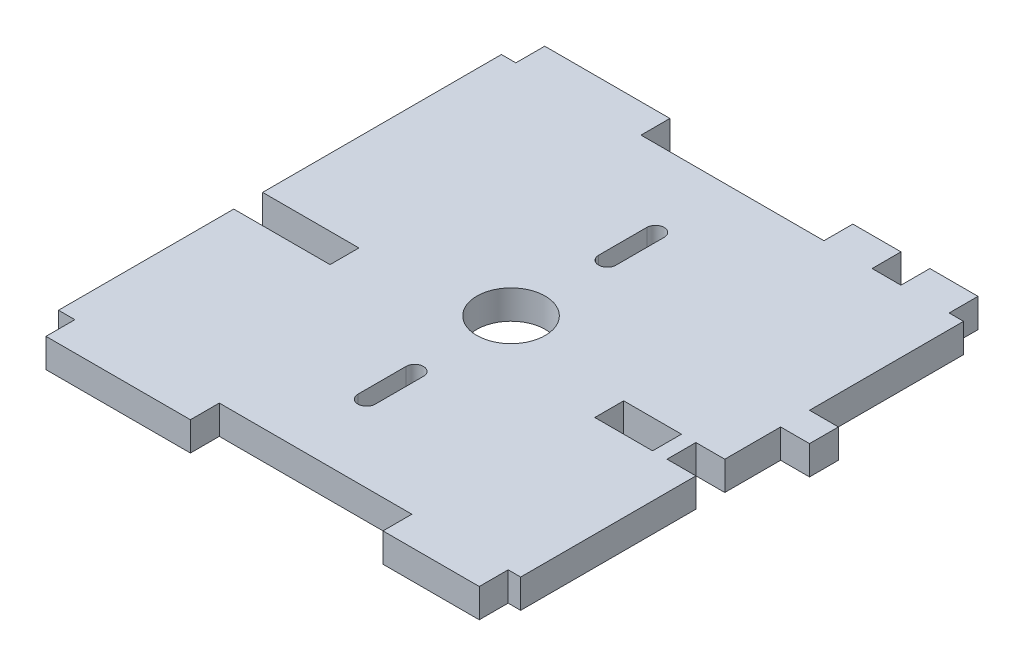
SolidWorks part; units mm, degrees
material "Acrílico (médio-alto impacto)"
ref_plane "Plano frontal" through (0, 0, 0) normal (0, 0, 1) x (1, 0, 0)
ref_plane "Plano superior" through (0, 0, 0) normal (0, 1, 0) x (1, 0, 0)
ref_plane "Plano direito" through (0, 0, 0) normal (1, 0, 0) x (0, 0, -1)
sketch "Esboço1" plane through (0, 0, 0) normal (0, 1, 0) x (1, 0, 0)
  line L1 (-24, -23) -> (24, -23)
  line L2 (-24, -23) -> (-24, 23)
  line L3 (-24, 23) -> (24, 23)
  line L4 (24, -23) -> (24, 23)
  line L5 (0, 23) -> (0, -23) construction
  line L6 (-24, 0) -> (24, 0) construction
  point P0 (0, 0)
  dimension "D1" = 46
  dimension "D2" = 48
sketch "Esboço2" plane through (0, 0, 0) normal (0, 1, 0) x (1, 0, 0)
  line L0 (0, 23) -> (0, -23) construction
  circle A0 centre (0, 0) radius 3.55
  dimension "D1" = 7.1
sketch "Esboço3" plane through (0, 0, 0) normal (0, 1, 0) x (1, 0, 0)
  line L0 (0, 10) -> (0, 15) construction
  line L1 (0, 23) -> (0, -23) construction
  line L2 (-0.9, 10) -> (-0.9, 15)
  line L3 (0.9, 10) -> (0.9, 15)
  arc A0 (-0.9, 10) -> (0.9, 10) centre (0, 10) ccw
  arc A1 (0.9, 15) -> (-0.9, 15) centre (0, 15) ccw
  circle A2 centre (0, 0) radius 12.5 construction
  point P4 (0, 12.5)
  dimension "D1" = 25
  dimension "D2" = 1.8
  dimension "D3" = 5
sketch "Esboço5" plane through (0, 0, 0) normal (0, 1, 0) x (1, 0, 0)
  line L0 (-24, 23) -> (24, 23) construction
  line L1 (22.5, 26) -> (17.5, 26)
  line L2 (22.5, 26) -> (22.5, 23)
  line L3 (22.5, 23) -> (17.5, 23)
  line L4 (17.5, 26) -> (17.5, 23)
  line L5 (14.5, 26) -> (9.5, 26)
  line L6 (14.5, 26) -> (14.5, 23)
  line L7 (14.5, 23) -> (9.5, 23)
  line L8 (9.5, 26) -> (9.5, 23)
  line L9 (-9.5, 26) -> (-22.5, 26)
  line L10 (-9.5, 26) -> (-9.5, 23)
  line L11 (-9.5, 23) -> (-22.5, 23)
  line L12 (-22.5, 26) -> (-22.5, 23)
  line L13 (-24, -23) -> (-24, 23) construction
  dimension "D1" = 1.5
  dimension "D2" = 1.5
  dimension "D3" = 3
  dimension "D4" = 5
  dimension "D5" = 3
  dimension "D6" = 13
sketch "Esboço6" plane through (0, 0, 0) normal (0, 1, 0) x (1, 0, 0)
  line L0 (24, -23) -> (24, 23) construction
  line L1 (24, 4) -> (27, 4)
  line L2 (24, 4) -> (24, 7)
  line L3 (24, 7) -> (27, 7)
  line L4 (27, 4) -> (27, 7)
  line L5 (-24, 23) -> (24, 23) construction
  dimension "D1" = 3
  dimension "D2" = 16
sketch "Esboço7" plane through (0, 0, 0) normal (0, 1, 0) x (1, 0, 0)
  line L0 (-24, -23) -> (-24, 23) construction
  line L1 (24, -4.8) -> (21, -4.8)
  line L2 (24, -4.8) -> (24, -1.8)
  line L3 (24, -1.8) -> (21, -1.8)
  line L4 (21, -4.8) -> (21, -1.8)
  line L5 (19.5, -4.8) -> (13.5, -4.8)
  line L6 (19.5, -4.8) -> (19.5, -1.8)
  line L7 (19.5, -1.8) -> (13.5, -1.8)
  line L8 (13.5, -4.8) -> (13.5, -1.8)
  line L9 (-14, -4.8) -> (-24, -4.8)
  line L10 (-14, -4.8) -> (-14, -1.8)
  line L11 (-14, -1.8) -> (-24, -1.8)
  line L12 (-24, -4.8) -> (-24, -1.8)
  line L13 (24, -23) -> (24, 23) construction
  line L19 (-24, -23) -> (24, -23) construction
  dimension "D1" = 3
  dimension "D2" = 18.2
  dimension "D3" = 10
  dimension "D4" = 3
  dimension "D5" = 1.5
  dimension "D6" = 6
extrude "Ressalto-extrusão1" add sketch "Esboço1" along normal blind 3 contours L2 L3 L4 L1
extrude "Ressalto-extrusão4" add sketch "Esboço6" along normal through all
extrude "Corte-extrusão1" cut sketch "Esboço2" along normal through all contours A0
extrude "Corte-extrusão2" cut sketch "Esboço3" along normal through all contours A1 L2 A0 L3
pattern_circular "PadrãoCircular1" count 2 over 360 about axis through (0, 0, 0) along (0, 1, 0) of "Corte-extrusão2"
sketch "Esboço4" plane through (0, 3, 0) normal (0, 1, 0) x (1, 0, 0)
  line L0 (-24, -23) -> (24, -23) construction
  line L1 (22.7, -23) -> (12.7, -23)
  line L2 (22.7, -23) -> (22.7, -26)
  line L3 (22.7, -26) -> (12.7, -26)
  line L4 (12.7, -23) -> (12.7, -26)
  line L6 (-22.3, -23) -> (-7.3, -23)
  line L7 (-22.3, -23) -> (-22.3, -26)
  line L8 (-22.3, -26) -> (-7.3, -26)
  line L9 (-7.3, -23) -> (-7.3, -26)
  line L10 (-24, -23) -> (-22.3, -23) construction
  line L11 (22.7, -23) -> (24, -23) construction
  line L12 (24, -23) -> (24, 4) construction
  dimension "D1" = 3
  dimension "D2" = 10
  dimension "D3" = 20
  dimension "D4" = 15
  dimension "D5" = 1.3
extrude "Ressalto-extrusão2" add sketch "Esboço4" against normal through all
extrude "Ressalto-extrusão3" add sketch "Esboço5" along normal through all
extrude "Corte-extrusão3" cut sketch "Esboço7" along normal through all
